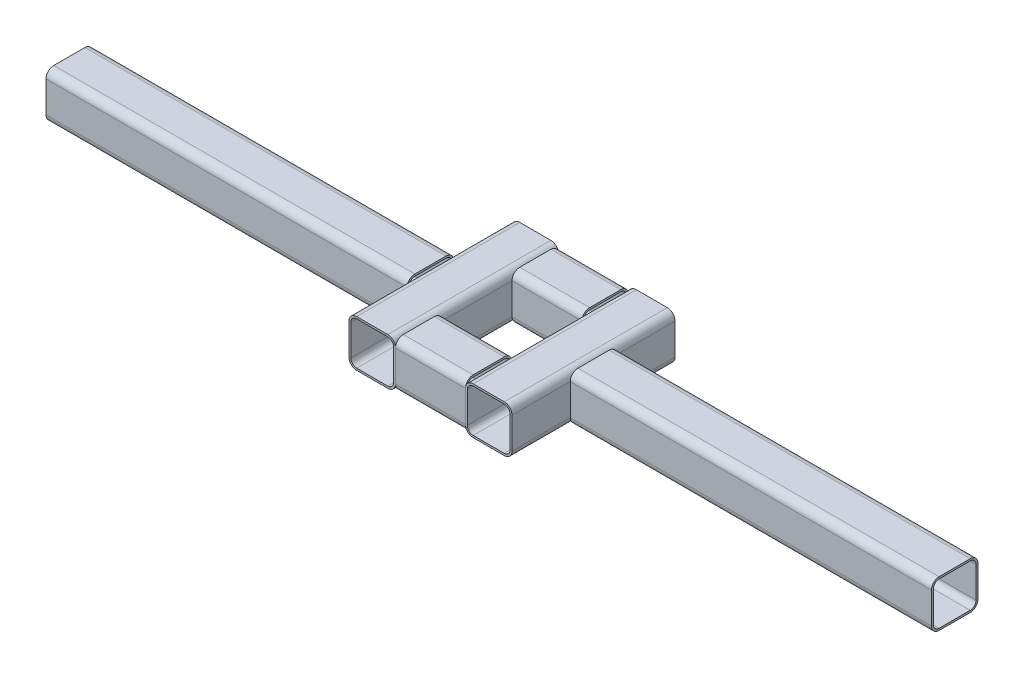
SolidWorks part; units mm, degrees
material "Plain Carbon Steel"
ref_plane "Front Plane" through (0, 0, 0) normal (0, 0, 1) x (1, 0, 0)
ref_plane "Top Plane" through (0, 0, 0) normal (0, 1, 0) x (1, 0, 0)
ref_plane "Right Plane" through (0, 0, 0) normal (1, 0, 0) x (0, 0, -1)
sketch "Sketch1" plane through (0, 0, 0) normal (0, 0, 1) x (1, 0, 0)
  line L0 (0, 0) -> (1447.8, 0)
  dimension "D1" = 1447.8
other "Structural Member1"
ref_plane "Plane1" through (0, 0, 0) normal (1, 0, 0) x (0, 1, 0)
sketch "Sketch11" plane through (0, 0, 0) normal (1, 0, 0) x (0, 1, 0)
  line L0 (-25.4, -34.925) -> (25.4, -34.925)
  line L1 (-34.925, -25.4) -> (-34.925, 25.4)
  line L2 (25.4, 34.925) -> (-25.4, 34.925)
  line L3 (34.925, 25.4) -> (34.925, -25.4)
  line L4 (-25.4, -38.1) -> (25.4, -38.1)
  line L5 (-38.1, -25.4) -> (-38.1, 25.4)
  line L6 (25.4, 38.1) -> (-25.4, 38.1)
  line L7 (38.1, 25.4) -> (38.1, -25.4)
  line L8 (0, 0) -> (34.925, 0) construction
  line L9 (0, 0) -> (0, 34.925) construction
  arc A0 (38.1, 25.4) -> (25.4, 38.1) centre (25.4, 25.4) ccw
  arc A1 (25.4, -38.1) -> (38.1, -25.4) centre (25.4, -25.4) ccw
  arc A2 (-38.1, -25.4) -> (-25.4, -38.1) centre (-25.4, -25.4) ccw
  arc A3 (-25.4, 38.1) -> (-38.1, 25.4) centre (-25.4, 25.4) ccw
  arc A4 (-25.4, 34.925) -> (-34.925, 25.4) centre (-25.4, 25.4) ccw
  arc A5 (34.925, 25.4) -> (25.4, 34.925) centre (25.4, 25.4) ccw
  arc A6 (25.4, -34.925) -> (34.925, -25.4) centre (25.4, -25.4) ccw
  arc A7 (-34.925, -25.4) -> (-25.4, -34.925) centre (-25.4, -25.4) ccw
  point P3 (0, 38.1)
  point P4 (38.1, 0)
  point P5 (0, -38.1)
  point P6 (-38.1, 0)
  point P7 (-38.1, 38.1)
  point P8 (-38.1, -38.1)
  point P33 (0, 0)
  point P35 (38.1, -38.1)
  point P36 (38.1, 38.1)
  point P37 (0, 0)
  dimension "D1" = 12.7
  dimension "Thickness" = 3.175
  dimension "V_leg" = 76.2
sketch "Sketch12" plane through (0, 0, -38.1) normal (0, 0, -1) x (-1, 0, 0)
  line L0 (0, -25.4) -> (0, 25.4) construction
  line L1 (-857.25, 38.1) -> (-590.55, 38.1)
  line L2 (-857.25, 38.1) -> (-857.25, -38.1)
  line L3 (-857.25, -38.1) -> (-590.55, -38.1)
  line L4 (-590.55, 38.1) -> (-590.55, -38.1)
  line L5 (-857.25, 38.1) -> (-590.55, -38.1) construction
  line L6 (-857.25, -38.1) -> (-590.55, 38.1) construction
  line L7 (-1447.8, 38.1) -> (0, 38.1) construction
  line L8 (-1447.8, -38.1) -> (0, -38.1) construction
  point P0 (-723.9, 0)
  dimension "D1" = 723.9
  dimension "D2" = 266.7
extrude "Cut-Extrude1" cut sketch "Sketch12" against normal through all
sketch "Sketch13" plane through (0, 0, 0) normal (0, 0, 1) x (1, 0, 0)
  line L0 (857.25, 25.4) -> (857.25, -25.4) construction
  line L1 (590.55, -25.4) -> (590.55, 25.4) construction
  line L2 (590.55, -38.1) -> (0, -38.1) construction
  point P0 (628.65, 0)
  point P1 (819.15, 0)
  point P2 (857.25, 0)
  dimension "D1" = 38.1
  dimension "D2" = 38.1
  dimension "D3" = 38.1
sketch "Sketch14" plane through (0, 0, 0) normal (0, 1, 0) x (1, 0, 0)
  line L2 (628.65, 133.35) -> (628.65, -133.35)
  line L4 (819.15, -133.35) -> (819.15, 133.35)
  dimension "D1" = 266.7
  dimension "D2" = 133.35
other "Structural Member2"
ref_plane "Plane2" through (628.65, 0, -133.35) normal (0, 0, 1) x (1, 0, 0)
sketch "Sketch15" plane through (628.65, 0, -133.35) normal (0, 0, 1) x (1, 0, 0)
  line L0 (-25.4, -34.925) -> (25.4, -34.925)
  line L1 (-34.925, -25.4) -> (-34.925, 25.4)
  line L2 (25.4, 34.925) -> (-25.4, 34.925)
  line L3 (34.925, 25.4) -> (34.925, -25.4)
  line L4 (-25.4, -38.1) -> (25.4, -38.1)
  line L5 (-38.1, -25.4) -> (-38.1, 25.4)
  line L6 (25.4, 38.1) -> (-25.4, 38.1)
  line L7 (38.1, 25.4) -> (38.1, -25.4)
  line L8 (0, 0) -> (34.925, 0) construction
  line L9 (0, 0) -> (0, 34.925) construction
  arc A0 (38.1, 25.4) -> (25.4, 38.1) centre (25.4, 25.4) ccw
  arc A1 (25.4, -38.1) -> (38.1, -25.4) centre (25.4, -25.4) ccw
  arc A2 (-38.1, -25.4) -> (-25.4, -38.1) centre (-25.4, -25.4) ccw
  arc A3 (-25.4, 38.1) -> (-38.1, 25.4) centre (-25.4, 25.4) ccw
  arc A4 (-25.4, 34.925) -> (-34.925, 25.4) centre (-25.4, 25.4) ccw
  arc A5 (34.925, 25.4) -> (25.4, 34.925) centre (25.4, 25.4) ccw
  arc A6 (25.4, -34.925) -> (34.925, -25.4) centre (25.4, -25.4) ccw
  arc A7 (-34.925, -25.4) -> (-25.4, -34.925) centre (-25.4, -25.4) ccw
  point P3 (0, 38.1)
  point P4 (38.1, 0)
  point P5 (0, -38.1)
  point P6 (-38.1, 0)
  point P7 (-38.1, 38.1)
  point P8 (-38.1, -38.1)
  point P33 (0, 0)
  point P35 (38.1, -38.1)
  point P36 (38.1, 38.1)
  point P37 (0, 0)
  dimension "D1" = 12.7
  dimension "Thickness" = 3.175
  dimension "V_leg" = 76.2
sketch "Sketch16" plane through (0, 0, 0) normal (0, 1, 0) x (1, 0, 0)
  line L0 (781.05, 95.25) -> (666.75, 95.25)
  line L1 (781.05, -133.35) -> (781.05, 133.35) construction
  line L2 (666.75, -133.35) -> (666.75, 133.35) construction
  line L3 (666.75, 95.25) -> (666.75, 133.35) construction
  line L4 (781.05, -95.25) -> (666.75, -95.25)
  line L5 (666.75, -95.25) -> (666.75, -133.35) construction
  dimension "D1" = 190.5
other "Structural Member3"
ref_plane "Plane3" through (781.05, 0, -95.25) normal (-1, 0, 0) x (0, 0, 1)
sketch "Sketch17" plane through (781.05, 0, -95.25) normal (-1, 0, 0) x (0, 0, 1)
  line L0 (-25.4, -34.925) -> (25.4, -34.925)
  line L1 (-34.925, -25.4) -> (-34.925, 25.4)
  line L2 (25.4, 34.925) -> (-25.4, 34.925)
  line L3 (34.925, 25.4) -> (34.925, -25.4)
  line L4 (-25.4, -38.1) -> (25.4, -38.1)
  line L5 (-38.1, -25.4) -> (-38.1, 25.4)
  line L6 (25.4, 38.1) -> (-25.4, 38.1)
  line L7 (38.1, 25.4) -> (38.1, -25.4)
  line L8 (0, 0) -> (34.925, 0) construction
  line L9 (0, 0) -> (0, 34.925) construction
  arc A0 (38.1, 25.4) -> (25.4, 38.1) centre (25.4, 25.4) ccw
  arc A1 (25.4, -38.1) -> (38.1, -25.4) centre (25.4, -25.4) ccw
  arc A2 (-38.1, -25.4) -> (-25.4, -38.1) centre (-25.4, -25.4) ccw
  arc A3 (-25.4, 38.1) -> (-38.1, 25.4) centre (-25.4, 25.4) ccw
  arc A4 (-25.4, 34.925) -> (-34.925, 25.4) centre (-25.4, 25.4) ccw
  arc A5 (34.925, 25.4) -> (25.4, 34.925) centre (25.4, 25.4) ccw
  arc A6 (25.4, -34.925) -> (34.925, -25.4) centre (25.4, -25.4) ccw
  arc A7 (-34.925, -25.4) -> (-25.4, -34.925) centre (-25.4, -25.4) ccw
  point P3 (0, 38.1)
  point P4 (38.1, 0)
  point P5 (0, -38.1)
  point P6 (-38.1, 0)
  point P7 (-38.1, 38.1)
  point P8 (-38.1, -38.1)
  point P33 (0, 0)
  point P35 (38.1, -38.1)
  point P36 (38.1, 38.1)
  point P37 (0, 0)
  dimension "D1" = 12.7
  dimension "Thickness" = 3.175
  dimension "V_leg" = 76.2
equation "\"D1@Sketch14\"=\"PDim\"+6"
equation "\"D2@Sketch14\"=\"PDim\"/2+3"
equation "\"D2@Sketch12\"=\"PDim\"+6"
equation "\"D1@Sketch16\"=\"PDim\"+3"
